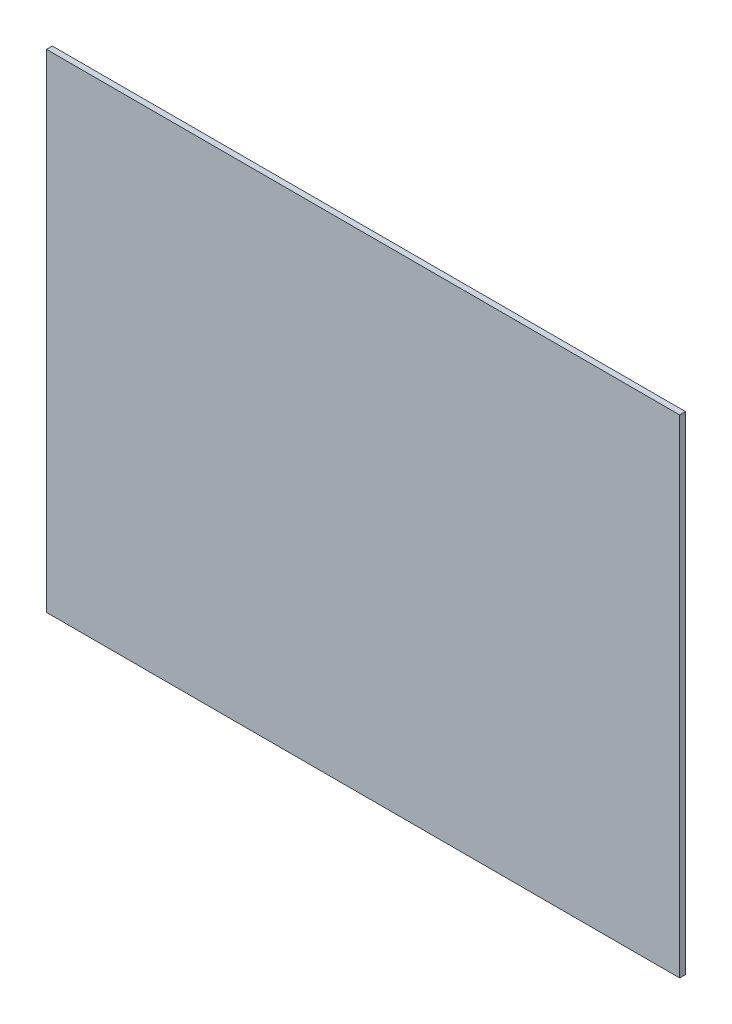
SolidWorks part; units mm, degrees
ref_plane "Ön Düzlem" through (0, 0, 0) normal (0, 0, 1) x (1, 0, 0)
ref_plane "Üst Düzlem" through (0, 0, 0) normal (0, 1, 0) x (1, 0, 0)
ref_plane "Sağ Düzlem" through (0, 0, 0) normal (1, 0, 0) x (0, 0, -1)
sketch "Sketch1" plane through (0, 0, 0) normal (0, 0, 1) x (1, 0, 0)
  line L1 (-217.5, 167.5) -> (217.5, 167.5)
  line L2 (-217.5, 167.5) -> (-217.5, -167.5)
  line L3 (-217.5, -167.5) -> (217.5, -167.5)
  line L4 (217.5, 167.5) -> (217.5, -167.5)
  line L5 (-217.5, 167.5) -> (217.5, -167.5) construction
  line L6 (-217.5, -167.5) -> (217.5, 167.5) construction
  point P0 (0, 0)
  dimension "D1" = 435
  dimension "D2" = 335
extrude "Boss-Extrude1" add sketch "Sketch1" along normal blind 4
